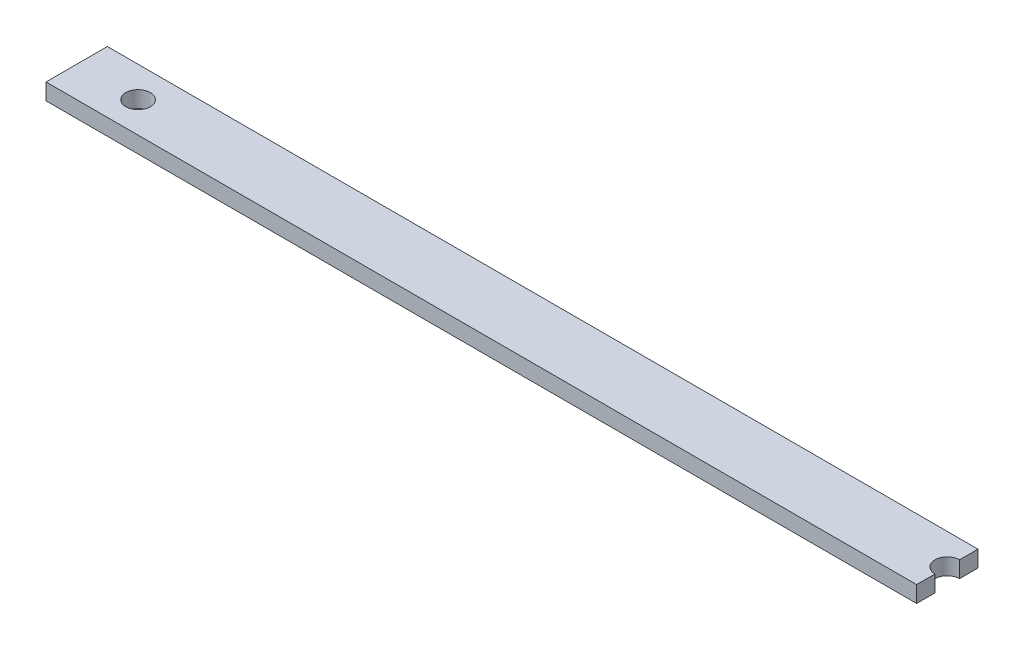
SolidWorks part; units mm, degrees
ref_plane "Front Plane" through (0, 0, 0) normal (0, 0, 1) x (1, 0, 0)
ref_plane "Top Plane" through (0, 0, 0) normal (0, 1, 0) x (1, 0, 0)
ref_plane "Right Plane" through (0, 0, 0) normal (1, 0, 0) x (0, 0, -1)
sketch "Sketch1" plane through (0, 0, 0) normal (0, 1, 0) x (1, 0, 0)
  line L1 (-106.375, -7.5) -> (106.375, -7.5)
  line L2 (-106.375, -7.5) -> (-106.375, 7.5)
  line L3 (-106.375, 7.5) -> (106.375, 7.5)
  line L4 (106.375, -7.5) -> (106.375, 7.5)
  line L5 (-106.375, -7.5) -> (106.375, 7.5) construction
  line L6 (-106.375, 7.5) -> (106.375, -7.5) construction
  point P0 (0, 0)
  dimension "D1" = 212.75
  dimension "D2" = 15
extrude "Boss-Extrude1" add sketch "Sketch1" along normal blind 4
sketch "Sketch2" plane through (0, 4, 0) normal (0, 1, 0) x (1, 0, 0)
  line L0 (106.375, -7.5) -> (106.375, 7.5) construction
  circle A0 centre (-91.375, 0) radius 5.2 construction
  circle A1 centre (-91.375, 0) radius 5.2 construction
  circle A2 centre (-91.375, 0) radius 3
  circle A3 centre (106.375, 0) radius 3
  point P8 (0, 0)
  dimension "D1" = 6
extrude "Cut-Extrude1" cut sketch "Sketch2" against normal through all
equation "\"D1@Sketch1\"=(851mm/4)"
